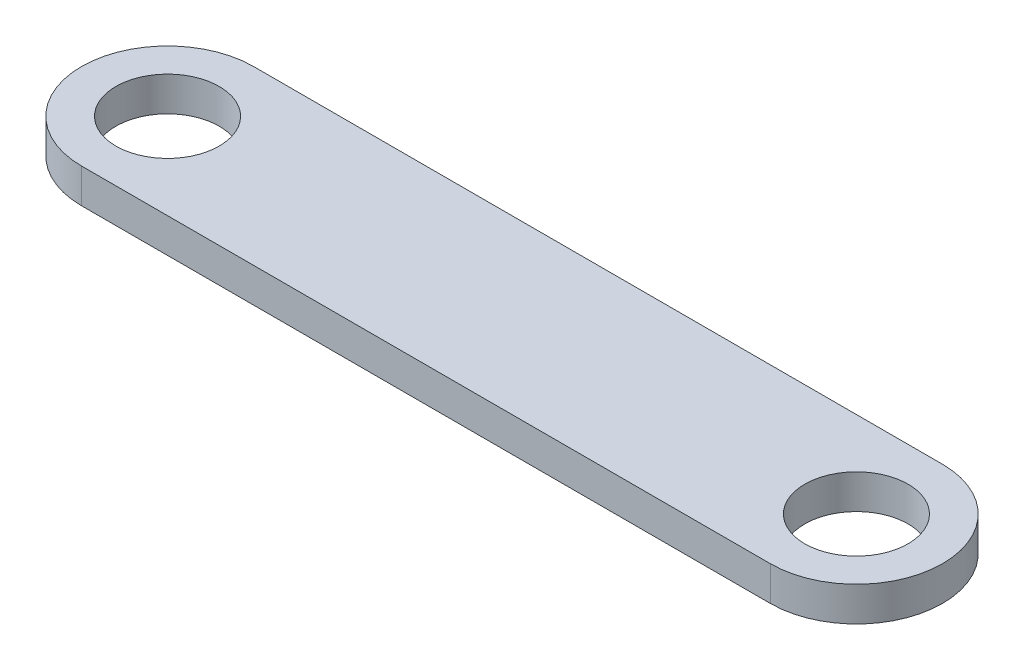
SolidWorks part; units mm, degrees
material "Cast Alloy Steel"
ref_plane "Front Plane" through (0, 0, 0) normal (0, 0, 1) x (1, 0, 0)
ref_plane "Top Plane" through (0, 0, 0) normal (0, 1, 0) x (1, 0, 0)
ref_plane "Right Plane" through (0, 0, 0) normal (1, 0, 0) x (0, 0, -1)
sketch "Sketch1" plane through (0, 0, 0) normal (0, 1, 0) x (1, 0, 0)
  line L0 (0, 0) -> (80, 0) construction
  line L1 (0, 10) -> (80, 10)
  line L2 (0, -10) -> (80, -10)
  arc A0 (0, 10) -> (0, -10) centre (0, 0) ccw
  arc A1 (80, -10) -> (80, 10) centre (80, 0) ccw
  circle A2 centre (0, 0) radius 6
  circle A3 centre (80, 0) radius 6
  point P3 (40, 0)
  dimension "D2" = 10
  dimension "D3" = 12
  dimension "D4" = 12
  dimension "D1" = 80
extrude "Boss-Extrude1" add sketch "Sketch1" along normal blind 4
